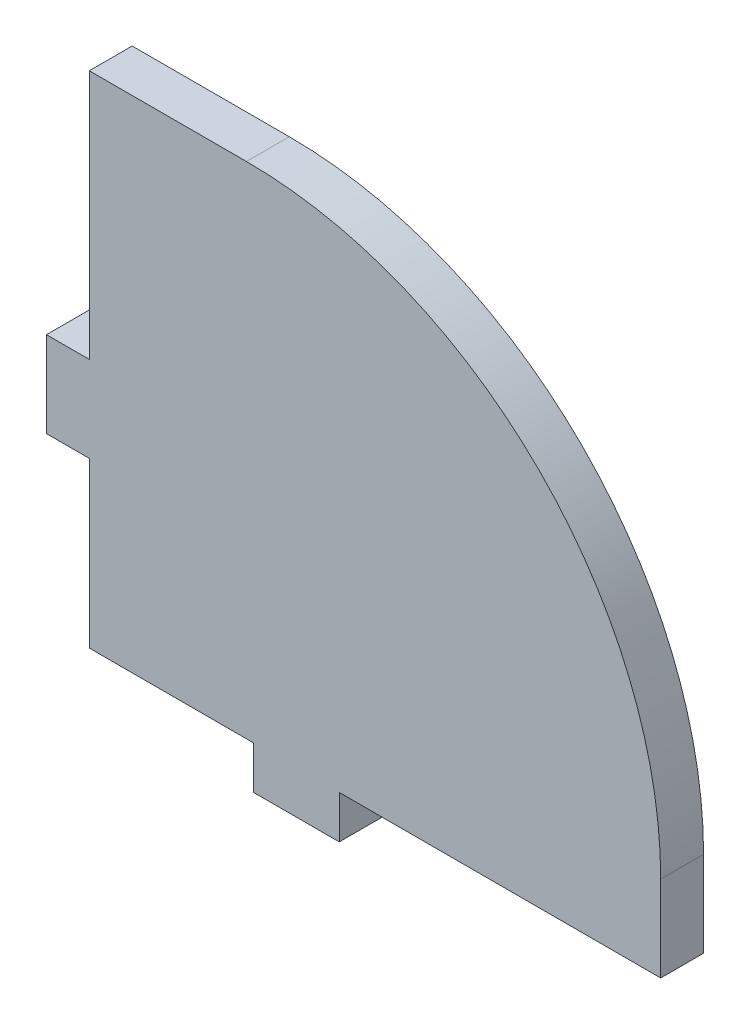
SolidWorks part; units mm, degrees
ref_plane "前视" through (0, 0, 0) normal (0, 0, 1) x (1, 0, 0)
ref_plane "上视" through (0, 0, 0) normal (0, 1, 0) x (1, 0, 0)
ref_plane "右视" through (0, 0, 0) normal (1, 0, 0) x (0, 0, -1)
sketch "草图1" plane through (0, 0, 0) normal (0, 0, 1) x (1, 0, 0)
  line L0 (0, 17.5) -> (-3, 17.5)
  line L1 (0, 0) -> (11.5, 0)
  line L2 (0, 0) -> (0, 11.5)
  line L3 (0, 35) -> (11, 35)
  line L4 (40, 0) -> (40, 6)
  line L5 (-3, 17.5) -> (-3, 11.5)
  line L6 (-3, 11.5) -> (0, 11.5)
  line L7 (11.5, 0) -> (11.5, -3)
  line L8 (11.5, -3) -> (17.5, -3)
  line L9 (17.5, -3) -> (17.5, 0)
  line L10 (0, 17.5) -> (0, 35)
  line L11 (17.5, 0) -> (40, 0)
  arc A0 (11, 35) -> (40, 6) centre (11, 6) cw
  dimension "D9" = 29
  dimension "D1" = 40
  dimension "D2" = 11.5
  dimension "D3" = 3
  dimension "D4" = 6
  dimension "D5" = 6
  dimension "D6" = 3
  dimension "D7" = 11.5
  dimension "D8" = 35
extrude "凸台-拉伸1" add sketch "草图1" along normal blind 3
